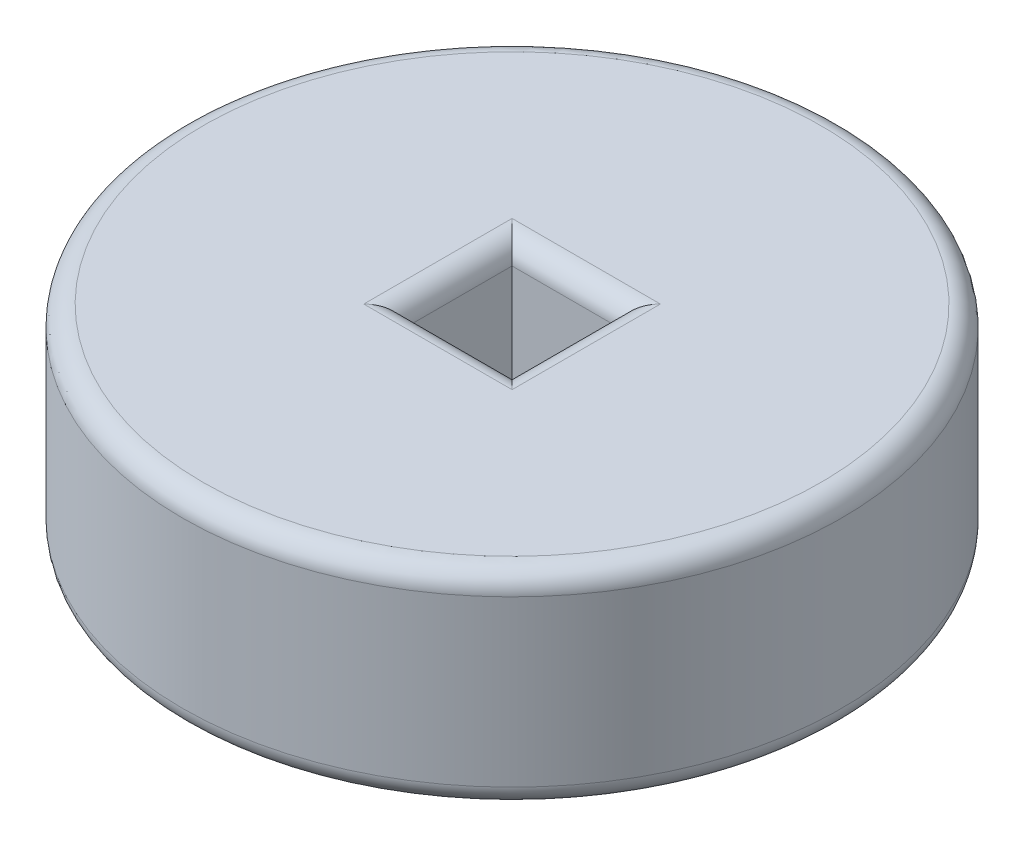
SolidWorks part; units mm, degrees
ref_plane "Front Plane" through (0, 0, 0) normal (0, 0, 1) x (1, 0, 0)
ref_plane "Top Plane" through (0, 0, 0) normal (0, 1, 0) x (1, 0, 0)
ref_plane "Right Plane" through (0, 0, 0) normal (1, 0, 0) x (0, 0, -1)
sketch "Sketch1" plane through (0, 0, 0) normal (0, 1, 0) x (1, 0, 0)
  line L1 (-3.302, -3.302) -> (3.302, -3.302)
  line L2 (-3.302, -3.302) -> (-3.302, 3.302)
  line L3 (-3.302, 3.302) -> (3.302, 3.302)
  line L4 (3.302, -3.302) -> (3.302, 3.302)
  line L5 (-3.302, -3.302) -> (3.302, 3.302) construction
  line L6 (-3.302, 3.302) -> (3.302, -3.302) construction
  circle A0 centre (0, 0) radius 20.32
  point P0 (0, 0)
  dimension "D1" = 40.64
  dimension "D2" = 6.604
extrude "Boss-Extrude1" add sketch "Sketch1" along normal blind 12.7
fillet "Fillet1" radius 1.27 10 edges at (0, 0, 3.302) (-3.302, 0, 0) (0, 0, -3.302) (3.302, 0, 0) (0, 0, 20.32) (-3.302, 12.7, 0) (0, 12.7, 3.302) (3.302, 12.7, 0) (0, 12.7, -3.302) (0, 12.7, 20.32)
